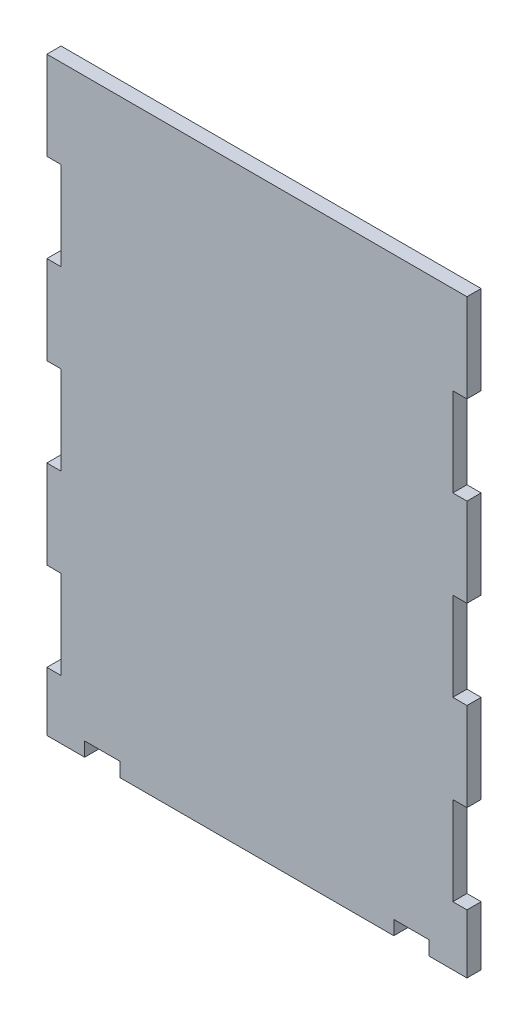
SolidWorks part; units mm, degrees
ref_plane "Front" through (0, 0, 0) normal (0, 0, 1) x (1, 0, 0)
ref_plane "Top" through (0, 0, 0) normal (0, 1, 0) x (1, 0, 0)
ref_plane "Right" through (0, 0, 0) normal (1, 0, 0) x (0, 0, -1)
sketch "Sketch1" plane through (0, 0, 0) normal (0, 0, 1) x (1, 0, 0)
  line L1 (0, 0) -> (-178, 0)
  line L2 (0, 0) -> (0, 250)
  line L3 (0, 250) -> (-178, 250)
  line L4 (-178, 0) -> (-178, 250)
  dimension "D1" = 250
  dimension "D2" = 178
extrude "Boss-Extrude1" add sketch "Sketch1" along normal blind 6
sketch "Sketch2" plane through (0, 0, 6) normal (0, 0, 1) x (1, 0, 0)
  line L0 (-178, 250) -> (-178, 0) construction
  line L1 (-178, 212.5) -> (-172, 212.5)
  line L2 (-178, 212.5) -> (-178, 175)
  line L3 (-178, 175) -> (-172, 175)
  line L4 (-172, 212.5) -> (-172, 175)
  line L5 (0, 250) -> (-178, 250) construction
  dimension "D1" = 37.5
  dimension "D2" = 37.5
  dimension "D3" = 6
extrude "Cut-Extrude1" cut sketch "Sketch2" against normal blind 6
pattern_linear "LPattern1" count 3 spacing 75 along (0, -1, 0) count 2 spacing 172 along (1, 0, 0) of "Cut-Extrude1"
sketch "Sketch3" plane through (0, 0, 6) normal (0, 0, 1) x (1, 0, 0)
  line L0 (-178, 0) -> (0, 0) construction
  line L1 (-16, 0) -> (-31, 0)
  line L2 (-16, 0) -> (-16, 6)
  line L3 (-16, 6) -> (-31, 6)
  line L4 (-31, 0) -> (-31, 6)
  line L5 (-89, 250) -> (-89, 0) construction
  line L6 (-6, 62.5) -> (-6, 25) construction
  line L7 (0, 250) -> (-178, 250) construction
  line L8 (-147, 0) -> (-147, 6)
  line L9 (-162, 6) -> (-147, 6)
  line L10 (-162, 0) -> (-162, 6)
  line L11 (-162, 0) -> (-147, 0)
  dimension "D1" = 15
  dimension "D2" = 10
  dimension "D3" = 6
extrude "Cut-Extrude2" cut sketch "Sketch3" against normal through all
